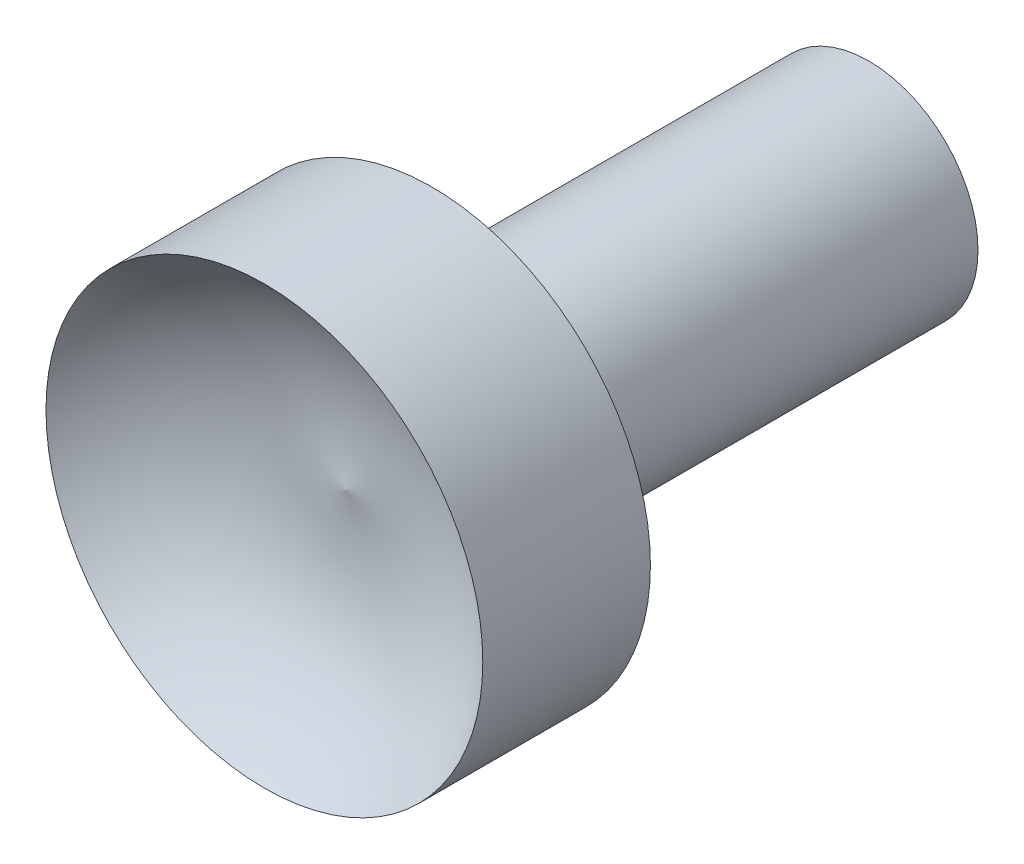
SolidWorks part; units mm, degrees
ref_plane "Front Plane" through (0, 0, 0) normal (0, 0, 1) x (1, 0, 0)
ref_plane "Top Plane" through (0, 0, 0) normal (0, 1, 0) x (1, 0, 0)
ref_plane "Right Plane" through (0, 0, 0) normal (1, 0, 0) x (0, 0, -1)
sketch "Sketch1" plane through (0, 0, 0) normal (0, 0, 1) x (1, 0, 0)
  line L0 (0, 87.7549) -> (0, -83.5304) construction
  line L1 (-127.1198, 0) -> (98.7003, 0) construction
  circle A0 centre (0, 0) radius 5
extrude "Boss-Extrude1" add sketch "Sketch1" along normal blind 6
sketch "Sketch3" plane through (0, 0, 0) normal (1, 0, 0) x (0, 0, -1)
  line L0 (0, 0) -> (-6, 0) construction
  line L1 (-6, 5) -> (-6, -5) construction
  line L2 (-6, 0) -> (-9.9572, 0)
  line L3 (-9.9572, 0) -> (-9.9572, 5.5144)
  line L5 (-6, 0) -> (-2, 0)
  line L6 (-6, 6) -> (-9.9572, 6)
  line L7 (-9.9572, 6) -> (-9.9572, 5.5144)
  arc A0 (-2, 0) -> (-6, 6) centre (-7, 1) ccw
revolve "Cut-Revolve1" cut sketch "Sketch3" angle 360 about L0
sketch "Sketch4" plane through (0, 0, 0) normal (0, 0, -1) x (-1, 0, 0)
  circle A0 centre (0, 0) radius 2.5
extrude "Boss-Extrude2" add sketch "Sketch4" along normal blind 10
